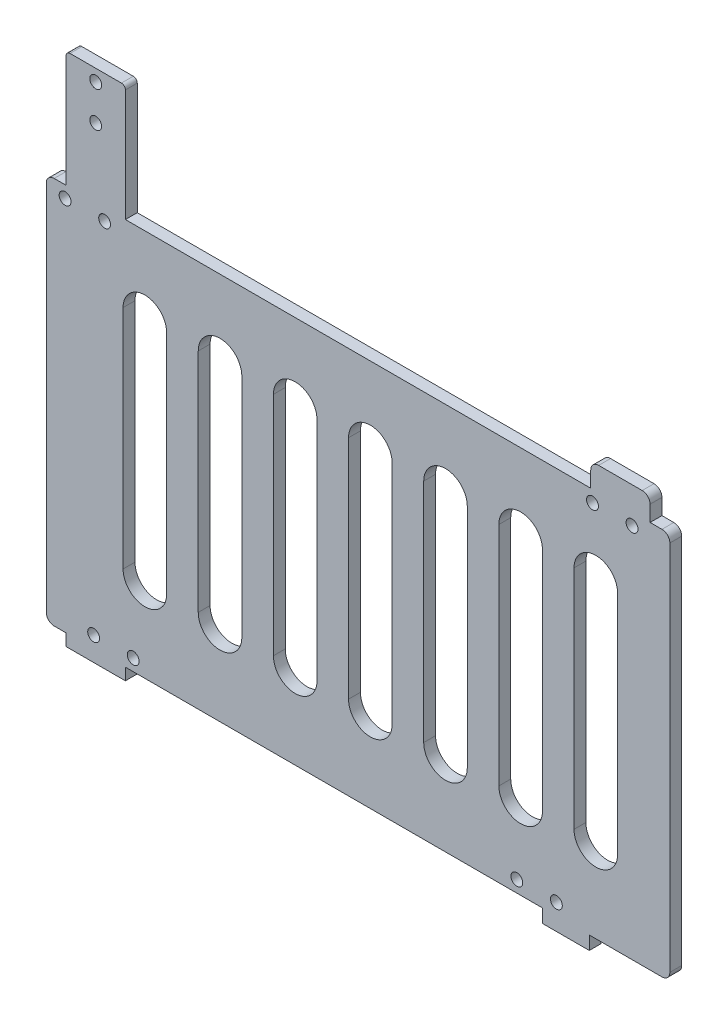
SolidWorks part; units mm, degrees
ref_plane "前视基准面" through (0, 0, 0) normal (0, 0, 1) x (1, 0, 0)
ref_plane "上视基准面" through (0, 0, 0) normal (0, 1, 0) x (1, 0, 0)
ref_plane "右视基准面" through (0, 0, 0) normal (1, 0, 0) x (0, 0, -1)
sketch "草图1" plane through (0, 0, 0) normal (0, 0, 1) x (1, 0, 0)
  line L0 (0, 0) -> (157.65, 0)
  line L2 (25, 104) -> (0, 104)
  line L3 (0, 104) -> (0, 0)
  line L4 (25, 104) -> (25, 101)
  line L6 (12.5, 104) -> (12.5, 89.1823) construction
  line L7 (5, 101) -> (0, 101)
  line L8 (5, 107) -> (20, 107)
  line L9 (5, 107) -> (5, 101)
  line L10 (5, 101) -> (20, 101)
  line L11 (20, 107) -> (20, 101)
  line L12 (5, 107) -> (20, 101) construction
  line L13 (5, 101) -> (20, 107) construction
  line L14 (20, 101) -> (25, 101)
  line L15 (-2.5, 120.5) -> (27.5, 120.5) construction
  line L16 (5, 101) -> (20, 101)
  line L17 (5, 101) -> (5, 108)
  line L18 (5, 108) -> (20, 108)
  line L19 (20, 101) -> (20, 108)
  line L20 (-2.5, 133) -> (27.5, 133)
  line L21 (-2.5, 108) -> (27.5, 108)
  line L22 (-2.5, 120.5) -> (27.5, 120.5) construction
  line L23 (-2.5, 128) -> (27.5, 128)
  line L24 (-2.5, 113) -> (27.5, 113)
  line L25 (25, 101) -> (137.65, 101)
  line L26 (157.65, 101) -> (157.65, 0)
  line L27 (78.825, 0) -> (78.825, 121.5588) construction
  line L29 (137.65, 107) -> (137.65, 101)
  line L30 (152.65, 107) -> (137.65, 107)
  line L31 (152.65, 107) -> (152.65, 101)
  line L32 (152.65, 101) -> (157.65, 101)
  arc A0 (-2.5, 133) -> (-2.5, 108) centre (-2.5, 120.5) ccw
  arc A1 (27.5, 108) -> (27.5, 133) centre (27.5, 120.5) ccw
  arc A2 (-2.5, 128) -> (-2.5, 113) centre (-2.5, 120.5) ccw
  arc A3 (27.5, 113) -> (27.5, 128) centre (27.5, 120.5) ccw
  point P18 (12.5, 120.5)
  point P23 (12.5, 108)
  point P24 (12.5, 108)
  point P27 (12.5, 120.5)
  dimension "D10" = 7.5
  dimension "D1" = 25
  dimension "D2" = 157.65
  dimension "D3" = 104
  dimension "D5" = 3
  dimension "D6" = 15
  dimension "D7" = 7
  dimension "D8" = 30
  dimension "D9" = 25
extrude "凸台-拉伸1" add sketch "草图1" along normal blind 3
sketch "草图2" plane through (0, 104, 0) normal (0, 1, 0) x (1, 0, 0)
  line L4 (20, 0) -> (5, 0)
  line L5 (5, 0) -> (5, -3)
  line L6 (5, -3) -> (20, -3)
  line L7 (20, -3) -> (20, 0)
  line L8 (20, 0) -> (5, 0)
  line L9 (5, 0) -> (5, -3)
  line L10 (5, -3) -> (20, -3)
  line L11 (20, -3) -> (20, 0)
  dimension "D1" = 0
extrude "凸台-拉伸2" add sketch "草图2" along normal blind 0.5
fillet "圆角4" radius 0.5 1 edges at (0, 0, 1.5)
sketch "草图6" plane through (0, 0, 3) normal (0, 0, 1) x (1, 0, 0)
  line L0 (0, 3) -> (152.6127, 3)
  line L1 (5, 3) -> (5, 0)
  line L2 (20, 3) -> (20, 0)
  line L3 (123.4743, 3) -> (123.4743, 0)
  line L4 (138.4743, 3) -> (138.4743, 0)
  line L9 (0, 101) -> (0, 0.5)
  line L10 (0.5, 0) -> (157.65, 0)
  line L11 (157.65, 0) -> (157.65, 101)
  line L12 (157.65, 0) -> (157.65, 101)
  line L13 (137.65, 101) -> (20, 101)
  line L14 (20, 101) -> (20, 104.5)
  line L15 (20, 104.5) -> (5, 104.5)
  line L16 (5, 104.5) -> (5, 101)
  line L17 (5, 101) -> (0, 101)
  line L18 (0, 101) -> (0, 0.5)
  line L19 (0.5, 0) -> (157.65, 0)
  line L22 (137.65, 101) -> (20, 101)
  line L23 (20, 101) -> (20, 104.5)
  line L24 (20, 104.5) -> (5, 104.5)
  line L25 (5, 104.5) -> (5, 101)
  line L26 (5, 101) -> (0, 101)
  line L35 (157.65, 101) -> (152.65, 101)
  line L36 (157.65, 101) -> (152.65, 101)
  line L37 (152.65, 101) -> (152.65, 107)
  line L38 (152.65, 101) -> (152.65, 107)
  line L39 (152.65, 107) -> (137.65, 107)
  line L40 (152.65, 107) -> (137.65, 107)
  line L41 (137.65, 107) -> (137.65, 101)
  line L42 (137.65, 107) -> (137.65, 101)
  arc A7 (0, 0.5) -> (0.5, 0) centre (0.5, 0.5) ccw
  arc A14 (0, 0.5) -> (0.5, 0) centre (0.5, 0.5) ccw
  dimension "D2" = 3
  dimension "D3" = 15
  dimension "D4" = 15
  dimension "D1" = 0
extrude "切除-拉伸3" cut sketch "草图6" against normal blind 10
sketch "草图10" plane through (0, 0, 0) normal (0, 0, -1) x (-1, 0, 0)
  line L14 (-157.65, 101) -> (-157.65, 0)
  line L15 (-157.65, 101) -> (-157.65, 0)
  line L16 (-157.65, 0) -> (-138.4743, 0)
  line L17 (-5, 3) -> (0, 3)
  line L18 (-20, 3) -> (-20, 0)
  line L19 (-20, 0) -> (-5, 0)
  line L20 (-5, 0) -> (-5, 3)
  line L21 (-5, 3) -> (0, 3)
  line L22 (0, 3) -> (0, 101)
  line L23 (0, 101) -> (-5, 101)
  line L24 (-5, 101) -> (-5, 104.5)
  line L25 (-5, 104.5) -> (-20, 104.5)
  line L26 (-20, 104.5) -> (-20, 101)
  line L27 (0, 101) -> (-5, 101)
  line L28 (-157.65, 0) -> (-138.4743, 0)
  line L29 (-20, 0) -> (-5, 0)
  line L30 (-20, 101) -> (-137.65, 101)
  line L31 (-138.4743, 0) -> (-138.4743, 3)
  line L32 (-20, 101) -> (-137.65, 101)
  line L33 (-138.4743, 3) -> (-20, 3)
  line L35 (-20, 3) -> (-20, 0)
  line L37 (-5, 0) -> (-5, 3)
  line L39 (0, 3) -> (0, 101)
  line L41 (-5, 101) -> (-5, 104.5)
  line L42 (-5, 104.5) -> (-20, 104.5)
  line L43 (-20, 104.5) -> (-20, 101)
  line L48 (-138.4743, 0) -> (-138.4743, 3)
  line L51 (-138.4743, 3) -> (-20, 3)
  line L56 (-137.65, 101) -> (-137.65, 107)
  line L57 (-137.65, 101) -> (-137.65, 107)
  line L58 (-137.65, 107) -> (-152.65, 107)
  line L59 (-137.65, 107) -> (-152.65, 107)
  line L60 (-152.65, 107) -> (-152.65, 101)
  line L61 (-152.65, 107) -> (-152.65, 101)
  line L62 (-152.65, 101) -> (-157.65, 101)
  line L63 (-152.65, 101) -> (-157.65, 101)
  circle A0 centre (-21.9705, 6) radius 1.5
  circle A1 centre (-11.9705, 6) radius 1.5
  dimension "D1" = 0
extrude "切除-拉伸7" cut sketch "草图10" against normal through all contours A0 | A1
sketch "草图11" plane through (0, 0, 0) normal (0, 0, -1) x (-1, 0, 0)
  circle A0 centre (-128.9587, 6) radius 1.5
  circle A1 centre (-118.9587, 6) radius 1.5
extrude "切除-拉伸8" cut sketch "草图11" against normal through all
sketch "草图15" plane through (0, 0, 0) normal (0, 0, -1) x (-1, 0, 0)
  line L0 (-20, 104.5) -> (-20, 101) construction
  line L1 (-5, 111.3775) -> (-20, 111.3775)
  line L2 (-5, 111.3775) -> (-5, 102.3775)
  line L3 (-5, 102.3775) -> (-20, 102.3775)
  line L4 (-20, 111.3775) -> (-20, 102.3775)
  dimension "D1" = 9
extrude "凸台-拉伸4" add sketch "草图15" against normal blind 3
fillet "圆角7" radius 1 2 edges at (5, 111.3775, 1.5) (20, 111.3775, 1.5)
sketch "草图16" plane through (0, 0, 3) normal (0, 0, 1) x (1, 0, 0)
  circle A0 centre (4.7529, 98) radius 1.5
  circle A1 centre (14.7529, 98) radius 1.5
extrude "切除-拉伸9" cut sketch "草图16" against normal through all
sketch "草图17" plane through (0, 0, 3) normal (0, 0, 1) x (1, 0, 0)
  line L1 (19, 130.3775) -> (6, 130.3775)
  line L2 (20, 129.3775) -> (20, 110.3775)
  line L3 (20, 110.3775) -> (5, 110.3775)
  line L4 (5, 129.3775) -> (5, 110.3775)
  arc A0 (19, 130.3775) -> (20, 129.3775) centre (19, 129.3775) cw
  arc A1 (6, 130.3775) -> (5, 129.3775) centre (6, 129.3775) ccw
  point P9 (5, 130.3775)
  dimension "D2" = 1
  dimension "D1" = 20
extrude "凸台-拉伸5" add sketch "草图17" against normal blind 3
sketch "草图18" plane through (0, 0, 0) normal (0, 0, -1) x (-1, 0, 0)
  line L0 (-138.9288, 81.4376) -> (-138.9288, 24.2012) construction
  line L1 (-133.4188, 81.4376) -> (-133.4188, 24.2012)
  line L2 (-144.4388, 81.4376) -> (-144.4388, 24.2012)
  line L3 (-119.9288, 81.4376) -> (-119.9288, 24.2012) construction
  line L4 (-114.4188, 81.4376) -> (-114.4188, 24.2012)
  line L5 (-125.4388, 81.4376) -> (-125.4388, 24.2012)
  line L6 (-100.9288, 81.4376) -> (-100.9288, 24.2012) construction
  line L7 (-95.4188, 81.4376) -> (-95.4188, 24.2012)
  line L8 (-106.4388, 81.4376) -> (-106.4388, 24.2012)
  line L9 (-81.9288, 81.4376) -> (-81.9288, 24.2012) construction
  line L10 (-76.4188, 81.4376) -> (-76.4188, 24.2012)
  line L11 (-87.4388, 81.4376) -> (-87.4388, 24.2012)
  line L12 (-62.9288, 81.4376) -> (-62.9288, 24.2012) construction
  line L13 (-57.4188, 81.4376) -> (-57.4188, 24.2012)
  line L14 (-68.4388, 81.4376) -> (-68.4388, 24.2012)
  line L15 (-43.9288, 81.4376) -> (-43.9288, 24.2012) construction
  line L16 (-38.4188, 81.4376) -> (-38.4188, 24.2012)
  line L17 (-49.4388, 81.4376) -> (-49.4388, 24.2012)
  line L18 (-24.9288, 81.4376) -> (-24.9288, 24.2012) construction
  line L19 (-19.4188, 81.4376) -> (-19.4188, 24.2012)
  line L20 (-30.4388, 81.4376) -> (-30.4388, 24.2012)
  arc A0 (-133.4188, 81.4376) -> (-144.4388, 81.4376) centre (-138.9288, 81.4376) ccw
  arc A1 (-144.4388, 24.2012) -> (-133.4188, 24.2012) centre (-138.9288, 24.2012) ccw
  arc A2 (-114.4188, 81.4376) -> (-125.4388, 81.4376) centre (-119.9288, 81.4376) ccw
  arc A3 (-125.4388, 24.2012) -> (-114.4188, 24.2012) centre (-119.9288, 24.2012) ccw
  arc A4 (-95.4188, 81.4376) -> (-106.4388, 81.4376) centre (-100.9288, 81.4376) ccw
  arc A5 (-106.4388, 24.2012) -> (-95.4188, 24.2012) centre (-100.9288, 24.2012) ccw
  arc A6 (-76.4188, 81.4376) -> (-87.4388, 81.4376) centre (-81.9288, 81.4376) ccw
  arc A7 (-87.4388, 24.2012) -> (-76.4188, 24.2012) centre (-81.9288, 24.2012) ccw
  arc A8 (-57.4188, 81.4376) -> (-68.4388, 81.4376) centre (-62.9288, 81.4376) ccw
  arc A9 (-68.4388, 24.2012) -> (-57.4188, 24.2012) centre (-62.9288, 24.2012) ccw
  arc A10 (-38.4188, 81.4376) -> (-49.4388, 81.4376) centre (-43.9288, 81.4376) ccw
  arc A11 (-49.4388, 24.2012) -> (-38.4188, 24.2012) centre (-43.9288, 24.2012) ccw
  arc A12 (-19.4188, 81.4376) -> (-30.4388, 81.4376) centre (-24.9288, 81.4376) ccw
  arc A13 (-30.4388, 24.2012) -> (-19.4188, 24.2012) centre (-24.9288, 24.2012) ccw
  point P2 (-138.9288, 52.8194)
  point P11 (-119.9288, 52.8194)
  point P18 (-100.9288, 52.8194)
  point P25 (-81.9288, 52.8194)
  point P32 (-62.9288, 52.8194)
  point P39 (-43.9288, 52.8194)
  point P46 (-24.9288, 52.8194)
  dimension "D1" = 7
extrude "切除-拉伸10" cut sketch "草图18" against normal blind 10
fillet "圆角8" radius 2 5 edges at (157.65, 101, 1.5) (0, 101, 1.5) (137.65, 107, 1.5) (152.65, 107, 1.5) (0, 3, 1.5)
sketch "草图19" plane through (0, 0, 3) normal (0, 0, 1) x (1, 0, 0)
  line L0 (138.4743, 3) -> (157.65, 3)
  line L1 (157.65, 99) -> (157.65, 0) construction
  line L2 (157.65, 3) -> (157.65, 0)
  line L3 (157.65, 0) -> (138.4743, 0)
  line L4 (138.4743, 0) -> (138.4743, 3)
extrude "切除-拉伸11" cut sketch "草图19" against normal blind 10
fillet "圆角9" radius 2 1 edges at (157.65, 3, 1.5)
sketch "草图20" plane through (0, 0, 3) normal (0, 0, 1) x (1, 0, 0)
  line L0 (125.51, 3) -> (125.51, -0.3999)
  line L1 (125.51, -0.3999) -> (137.2773, -0.3999)
  line L2 (137.2773, -0.3999) -> (137.2773, 3)
  line L3 (137.2773, 3) -> (125.51, 3)
  line L16 (20, 3) -> (155.65, 3)
  line L17 (157.65, 5) -> (157.65, 99)
  line L18 (155.65, 101) -> (152.65, 101)
  line L19 (152.65, 101) -> (152.65, 105)
  line L20 (150.65, 107) -> (139.65, 107)
  line L21 (137.65, 105) -> (137.65, 101)
  line L22 (137.65, 101) -> (20, 101)
  line L23 (20, 101) -> (20, 129.3775)
  line L24 (19, 130.3775) -> (6, 130.3775)
  line L25 (5, 129.3775) -> (5, 101)
  line L26 (5, 101) -> (2, 101)
  line L27 (0, 99) -> (0, 5)
  line L28 (2, 3) -> (5, 3)
  line L29 (5, 3) -> (5, 0)
  line L30 (5, 0) -> (20, 0)
  line L31 (20, 0) -> (20, 3)
  line L32 (20, 3) -> (155.65, 3)
  line L33 (157.65, 5) -> (157.65, 99)
  line L34 (155.65, 101) -> (152.65, 101)
  line L35 (152.65, 101) -> (152.65, 105)
  line L36 (150.65, 107) -> (139.65, 107)
  line L37 (137.65, 105) -> (137.65, 101)
  line L38 (137.65, 101) -> (20, 101)
  line L39 (20, 101) -> (20, 129.3775)
  line L40 (19, 130.3775) -> (6, 130.3775)
  line L41 (5, 129.3775) -> (5, 101)
  line L42 (5, 101) -> (2, 101)
  line L43 (0, 99) -> (0, 5)
  line L44 (2, 3) -> (5, 3)
  line L45 (5, 3) -> (5, 0)
  line L46 (5, 0) -> (20, 0)
  line L47 (20, 0) -> (20, 3)
  arc A8 (155.65, 3) -> (157.65, 5) centre (155.65, 5) ccw
  arc A9 (157.65, 99) -> (155.65, 101) centre (155.65, 99) ccw
  arc A10 (152.65, 105) -> (150.65, 107) centre (150.65, 105) ccw
  arc A11 (139.65, 107) -> (137.65, 105) centre (139.65, 105) ccw
  arc A12 (20, 129.3775) -> (19, 130.3775) centre (19, 129.3775) ccw
  arc A13 (6, 130.3775) -> (5, 129.3775) centre (6, 129.3775) ccw
  arc A14 (2, 101) -> (0, 99) centre (2, 99) ccw
  arc A15 (0, 5) -> (2, 3) centre (2, 5) ccw
  arc A16 (155.65, 3) -> (157.65, 5) centre (155.65, 5) ccw
  arc A17 (157.65, 99) -> (155.65, 101) centre (155.65, 99) ccw
  arc A18 (152.65, 105) -> (150.65, 107) centre (150.65, 105) ccw
  arc A19 (139.65, 107) -> (137.65, 105) centre (139.65, 105) ccw
  arc A20 (20, 129.3775) -> (19, 130.3775) centre (19, 129.3775) ccw
  arc A21 (6, 130.3775) -> (5, 129.3775) centre (6, 129.3775) ccw
  arc A22 (2, 101) -> (0, 99) centre (2, 99) ccw
  arc A23 (0, 5) -> (2, 3) centre (2, 5) ccw
  dimension "D1" = 0
extrude "凸台-拉伸6" add sketch "草图20" against normal blind 3 contours L2 L3 L0 L1
sketch "草图21" plane through (0, 0, 0) normal (0, 0, -1) x (-1, 0, 0)
  line L0 (-12.5, 130.3775) -> (-12.5, 111.8185) construction
  line L1 (-19, 130.3775) -> (-6, 130.3775) construction
  circle A0 centre (-12.5, 127.3775) radius 1.5
  circle A1 centre (-12.5, 118.3775) radius 1.5
  dimension "D1" = 3
  dimension "D3" = 3
  dimension "D2" = 3
  dimension "D4" = 9
extrude "切除-拉伸12" cut sketch "草图21" against normal blind 10
sketch "草图23" plane through (0, 0, 3) normal (0, 0, 1) x (1, 0, 0)
  circle A2 centre (148.0927, 98) radius 1.5
  circle A3 centre (138.0927, 98) radius 1.5
extrude "切除-拉伸13" cut sketch "草图23" against normal blind 10
